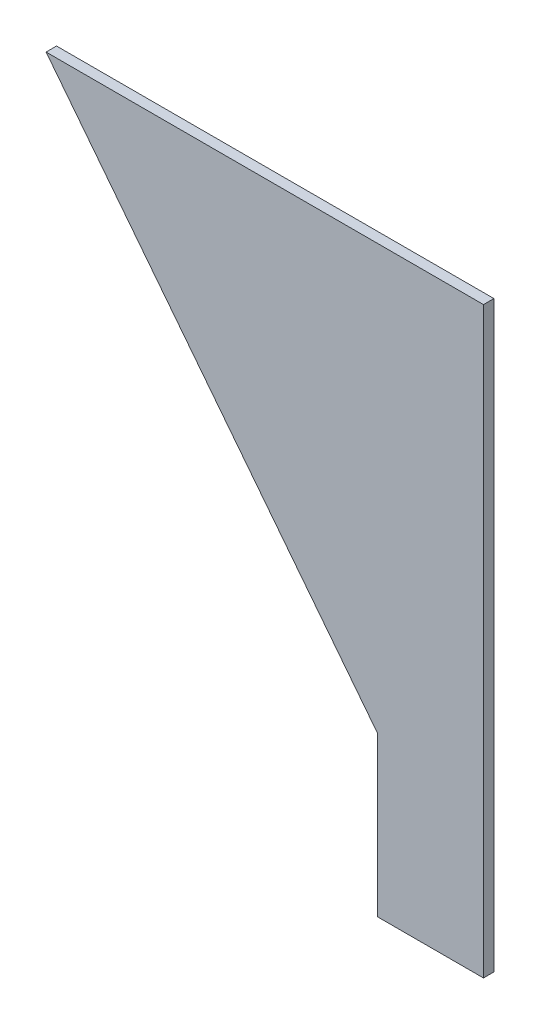
SolidWorks part; units mm, degrees
material "有机玻璃 (TM) GS 丙烯酸铸钣"
ref_plane "Front" through (0, 0, 0) normal (0, 0, 1) x (1, 0, 0)
ref_plane "Top" through (0, 0, 0) normal (0, 1, 0) x (1, 0, 0)
ref_plane "Right" through (0, 0, 0) normal (1, 0, 0) x (0, 0, -1)
sketch "草图1" plane through (0, 0, 0) normal (0, 0, 1) x (1, 0, 0)
  line L0 (0, 0) -> (0, 226.6654) construction
  line L1 (-95.25, 0) -> (-95.25, -76.2)
  line L2 (-146.05, 0) -> (-304.8, 203.2)
  line L3 (-304.8, 203.2) -> (-95.25, 203.2)
  line L4 (-95.25, 203.2) -> (-95.25, 0)
  line L5 (-95.25, 332.4166) -> (-95.25, -101.1205) construction
  line L6 (-146.05, 0) -> (-146.05, -76.2)
  line L7 (-146.05, -76.2) -> (-95.25, -76.2)
  point P7 (0, 0)
  point P8 (0, 203.2)
  dimension "D1" = 95.25
  dimension "D2" = 50.8
  dimension "D4" = 209.55
  dimension "D5" = 76.2
  dimension "D3" = 203.2
extrude "凸台-拉伸1" add sketch "草图1" along normal blind 5
equation "\"D4@草图1\"=12-\"D1@草图1\""
